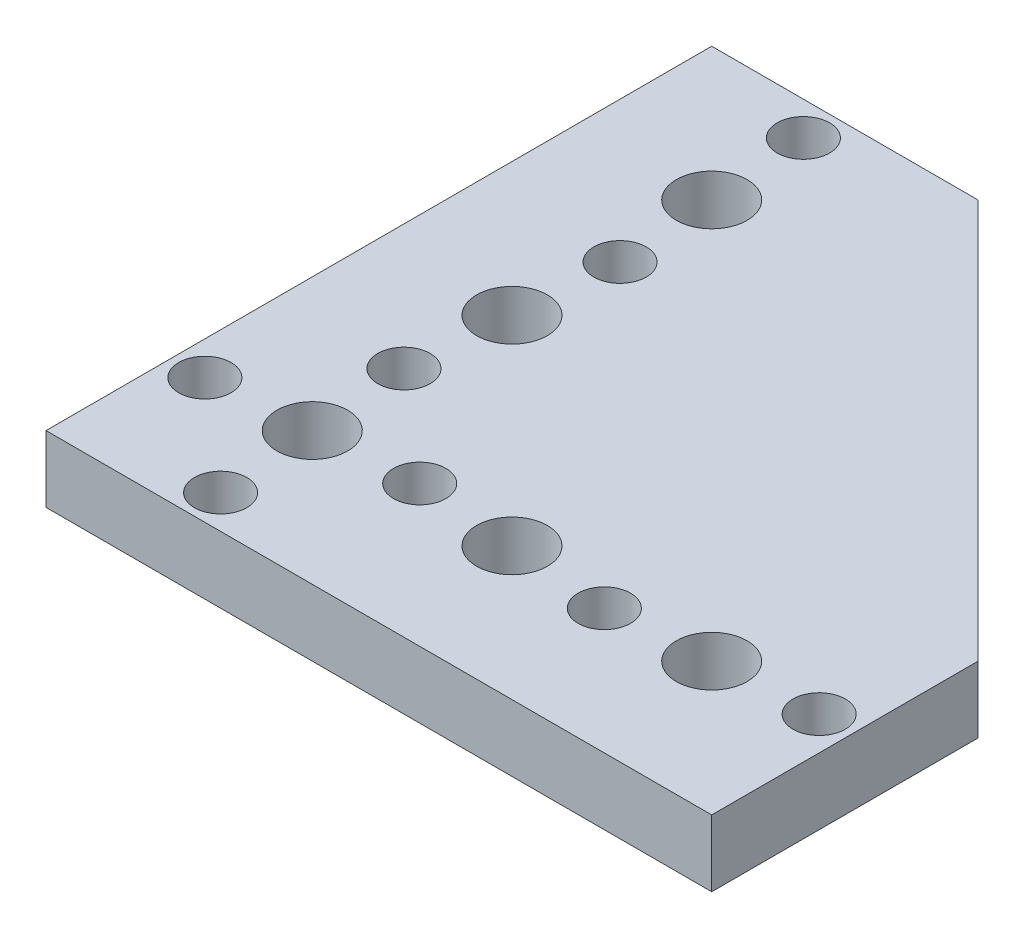
SolidWorks part; units mm, degrees
ref_plane "Front Plane" through (0, 0, 0) normal (0, 0, 1) x (1, 0, 0)
ref_plane "Top Plane" through (0, 0, 0) normal (0, 1, 0) x (1, 0, 0)
ref_plane "Right Plane" through (0, 0, 0) normal (1, 0, 0) x (0, 0, -1)
ref_plane "Plane1" through (0, 6.35, 0) normal (0, 1, 0) x (1, 0, 0)
sketch "Sketch1" plane through (0, 6.35, 0) normal (0, 1, 0) x (1, 0, 0)
  line L0 (25.4, 63.5) -> (0, 63.5)
  line L1 (0, 63.5) -> (0, 0)
  line L2 (0, 0) -> (63.5, 0)
  line L3 (63.5, 0) -> (63.5, 25.4)
  line L4 (63.5, 25.4) -> (25.4, 63.5)
  circle A0 centre (13.4512, 41.3047) radius 2.5
  circle A1 centre (11.9488, 60.2953) radius 2.5
  circle A2 centre (11.9488, 22.1953) radius 2.5
  circle A3 centre (13.4512, 3.2047) radius 2.5
  circle A4 centre (22.1953, 13.4512) radius 2.5
  circle A5 centre (3.2047, 11.9488) radius 2.5
  circle A6 centre (41.3047, 11.9488) radius 2.5
  circle A7 centre (60.2953, 13.4512) radius 2.5
  circle A8 centre (12.7, 50.8) radius 3.375
  circle A9 centre (12.7, 31.75) radius 3.375
  circle A10 centre (50.8, 12.7) radius 3.375
  circle A11 centre (31.75, 12.7) radius 3.375
  circle A12 centre (12.7, 12.7) radius 3.375
extrude "Boss-Extrude1" add sketch "Sketch1" against normal blind 6.35
